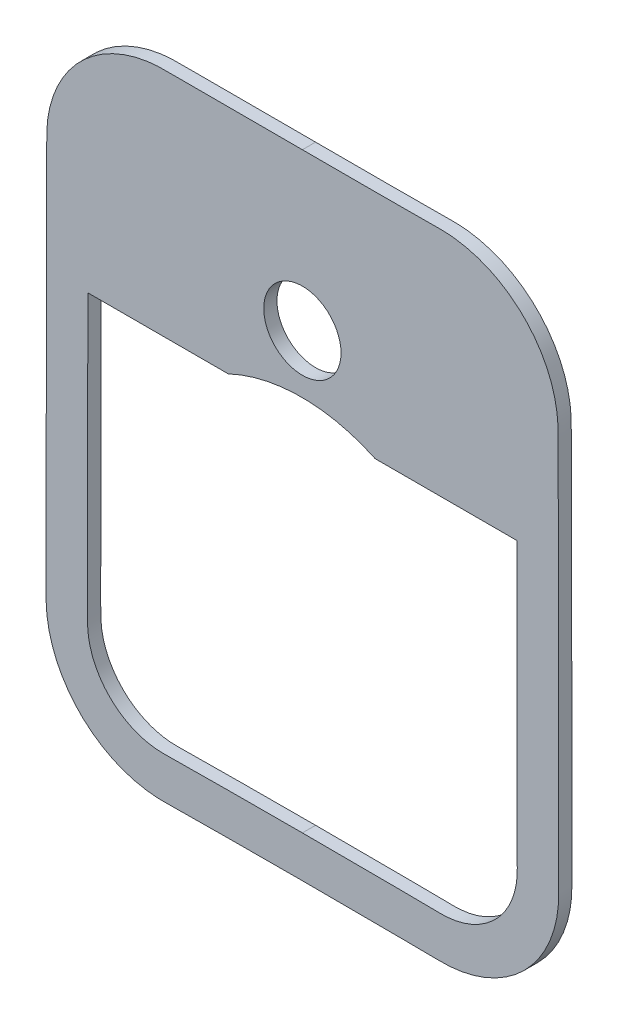
SolidWorks part; units mm, degrees
material "Фанера"
ref_plane "Front Plane" through (0, 0, 0) normal (0, 0, 1) x (1, 0, 0)
ref_plane "Top Plane" through (0, 0, 0) normal (0, 1, 0) x (1, 0, 0)
ref_plane "Right Plane" through (0, 0, 0) normal (1, 0, 0) x (0, 0, -1)
sketch "Эскиз1" plane through (0, 0, 0) normal (0, 0, 1) x (1, 0, 0)
  line L0 (-45.5461, 87.8348) -> (-15.7339, 87.8348)
  line L1 (15.434, 87.8348) -> (45.5461, 87.8348)
  circle A1 centre (0, 103.6369) radius 5.3081 construction
  circle A2 centre (0, 103.6369) radius 8.2
  arc A3 (15.434, 87.8348) -> (-15.7339, 87.8348) centre (-0.1499, 54.9069) ccw
  spline S2 degree 3 poles (0, 136.1045) (-1.239, 136.1005) (-3.4812, 136.0933) (-6.8233, 136.088) (-10.0686, 136.0864) (-13.4447, 136.0887) (-16.829, 136.0949) (-20.1617, 136.1046) (-23.5121, 136.1176) (-26.2938, 136.1309) (-28.566, 136.1434) (-29.8936, 136.1508) (-31.0537, 136.0882) (-32.1737, 135.9898) (-34.2507, 135.6881) (-36.962, 134.9957) (-40.5448, 133.5311) (-44.1262, 131.3165) (-47.4363, 128.2452) (-49.8603, 125.0096) (-51.5505, 121.7952) (-52.4886, 119.1589) (-53.011, 117.0051) (-53.2597, 115.5274) (-53.3997, 114.2038) (-53.4667, 113.0773) (-53.471, 112.0145) (-53.4746, 110.9498) (-53.4785, 109.8154) (-53.4833, 108.4239) (-53.4925, 105.7023) (-53.5036, 102.2993) (-53.5196, 97.2001) (-53.5364, 91.538) (-53.5543, 84.7858) (-53.5702, 77.9771) (-53.5877, 68.9188) (-53.602, 57.5219) (-53.6068, 47.3771) (-53.6075, 40.6409) (-53.6074, 37.3029) (-53.607, 33.8361) (-53.6056, 31.1139) (-53.6056, 29.1689) (-53.6031, 28.0347) (-53.6112, 26.7796) (-53.557, 25.5233) (-53.4451, 24.3914) (-53.1914, 22.5697) (-52.5939, 20.0135) (-51.2863, 16.6996) (-49.5197, 13.6361) (-47.2969, 10.8371) (-44.7104, 8.4168) (-41.7685, 6.386) (-38.5802, 4.8214) (-35.772, 3.927) (-33.4615, 3.4583) (-31.7903, 3.2468) (-30.0031, 3.1418) (-28.4368, 3.1717) (-26.9773, 3.1851) (-25.8041, 3.1977) (-23.8503, 3.2174) (-19.9413, 3.254) (-14.0761, 3.2944) (-8.2109, 3.3181) (-3.5189, 3.3246) (-1.173, 3.3237) (0, 3.3232) knots 0 0 0 0 0.016944 0.030662 0.045705 0.061325 0.076832 0.091987 0.106901 0.12265 0.130027 0.137979 0.140797 0.145912 0.153349 0.169481 0.184029 0.206151 0.226649 0.24543 0.261159 0.276148 0.283562 0.291448 0.296618 0.30176 0.306873 0.311149 0.316321 0.322385 0.330179 0.353541 0.368923 0.399912 0.430974 0.461263 0.493024 0.55485 0.61712 0.631758 0.64697 0.66277 0.679167 0.684198 0.689368 0.694679 0.70136 0.706552 0.710228 0.726511 0.7423 0.758789 0.774686 0.791009 0.80705 0.823397 0.8394 0.847199 0.855617 0.862414 0.871663 0.877028 0.882376 0.887707 0.90375 0.935835 0.967918 0.983959 1 1 1 1 construction
  spline S3 degree 3 poles (0, 3.3232) (1.137, 3.3237) (3.411, 3.3246) (7.9589, 3.3186) (12.568, 3.3008) (17.1159, 3.2733) (19.9367, 3.2523) (22.1494, 3.2332) (23.7247, 3.2185) (25.4517, 3.2014) (27.0575, 3.1842) (28.6039, 3.169) (29.7408, 3.1532) (30.8236, 3.1871) (31.9058, 3.2668) (33.0392, 3.4068) (34.8562, 3.7148) (37.397, 4.3882) (40.5436, 5.7219) (43.4912, 7.5042) (46.1307, 9.6661) (48.4515, 12.1944) (50.3766, 15.0068) (51.8999, 18.0934) (52.7772, 20.776) (53.2576, 23.0208) (53.4959, 24.7163) (53.6141, 26.4623) (53.6032, 27.9573) (53.6057, 29.3141) (53.6056, 30.6272) (53.6063, 32.0893) (53.6067, 33.6016) (53.6074, 36.8843) (53.6078, 44.2661) (53.6034, 55.7555) (53.5877, 69.5428) (53.5639, 81.0461) (53.54, 90.2376) (53.5223, 96.3284) (53.5057, 101.6388) (53.4909, 106.2346) (53.4794, 109.4872) (53.4731, 111.3988) (53.4706, 111.9699) (53.4708, 112.6573) (53.4454, 113.462) (53.3764, 114.4711) (53.2466, 115.5902) (53.0551, 116.7225) (52.6709, 118.4974) (51.883, 121.0078) (49.9426, 125.0318) (46.3561, 129.6525) (41.6689, 133.0142) (37.3179, 134.8795) (34.2664, 135.7038) (31.9363, 136.025) (30.5022, 136.122) (29.6264, 136.1507) (28.7596, 136.1442) (27.9312, 136.1399) (26.6088, 136.1326) (24.8092, 136.1237) (22.5484, 136.1138) (19.9534, 136.1041) (16.9679, 136.0953) (13.5551, 136.0889) (10.1506, 136.0863) (6.8791, 136.0879) (3.51, 136.0932) (1.2495, 136.1005) (0, 136.1045) knots 0 0 0 0 0.015551 0.031101 0.062202 0.07859 0.093303 0.100784 0.108854 0.114851 0.124405 0.130817 0.136003 0.139953 0.145631 0.150838 0.155566 0.170832 0.186659 0.20215 0.217786 0.233163 0.248936 0.264236 0.280092 0.287391 0.295615 0.303487 0.311301 0.316057 0.322045 0.32926 0.336053 0.342729 0.374158 0.437014 0.499871 0.562728 0.594345 0.625584 0.646032 0.666977 0.688441 0.690519 0.693122 0.696252 0.699919 0.704131 0.710083 0.71532 0.71983 0.734917 0.751172 0.780732 0.813908 0.82875 0.845335 0.856962 0.860863 0.864992 0.868942 0.872718 0.876322 0.887028 0.897332 0.907244 0.92252 0.938164 0.953922 0.969083 0.98291 1 1 1 1 construction
  spline S4 degree 1 poles (0, 11.3232) (0, 128.1045) knots 0 0 1 1 construction
  spline S5 degree 1 poles (0, 128.1045) (0, 11.3232) knots 0 0 1 1 construction
  spline S6 degree 3 poles (0, 11.3232) (2.2914, 11.3241) (6.8725, 11.3235) (12.6076, 11.3006) (17.1907, 11.273) (20.6304, 11.2473) (23.4945, 11.2214) (25.5015, 11.2012) (26.6445, 11.1892) (27.4981, 11.1803) (28.3526, 11.1721) (29.2615, 11.1598) (29.839, 11.1589) (30.5951, 11.1877) (31.5601, 11.2733) (33.0632, 11.5165) (34.9112, 12.0213) (37.7182, 13.2396) (40.8423, 15.4848) (43.2085, 18.527) (44.5303, 21.281) (45.1061, 23.1124) (45.4051, 24.6024) (45.5267, 25.5545) (45.5832, 26.321) (45.6035, 26.858) (45.6071, 27.5423) (45.6037, 28.4431) (45.6056, 29.3042) (45.6057, 30.4331) (45.6062, 31.8704) (45.6067, 33.5791) (45.6072, 35.8647) (45.6075, 38.7185) (45.6074, 42.1445) (45.6068, 45.57) (45.6053, 50.1374) (45.602, 55.8464) (45.5955, 62.6969) (45.5861, 69.5469) (45.5735, 76.397) (45.5611, 81.9221) (45.5502, 86.3057) (45.5431, 88.9766) (45.5331, 92.5859) (45.5226, 96.1952) (45.5096, 100.376) (45.4987, 103.8012) (45.4893, 106.6586) (45.4812, 108.9361) (45.4768, 110.3823) (45.4721, 111.4889) (45.4715, 112.2716) (45.4666, 112.6362) (45.4544, 113.016) (45.4264, 113.485) (45.3721, 114.0493) (45.2726, 114.7975) (45.0279, 116.0922) (44.4738, 117.9106) (43.1792, 120.6556) (40.8322, 123.7098) (37.6799, 125.9932) (34.8772, 127.2283) (33.0188, 127.7525) (31.5003, 128.0116) (30.5513, 128.1064) (29.7599, 128.144) (29.2425, 128.1486) (28.3287, 128.1414) (27.2054, 128.1361) (25.7635, 128.1282) (23.4788, 128.1177) (20.6144, 128.106) (17.18, 128.0957) (12.599, 128.0869) (6.871, 128.0852) (2.2905, 128.0971) (0, 128.1045) knots 0.000014 0.000014 0.000014 0.000014 0.03126 0.062506 0.078129 0.093752 0.109375 0.117186 0.121092 0.124998 0.128903 0.132809 0.136715 0.140621 0.148432 0.156244 0.171867 0.187489 0.218735 0.249981 0.265604 0.281227 0.289039 0.29685 0.300756 0.304661 0.308567 0.312473 0.316379 0.320284 0.328096 0.335907 0.343719 0.359342 0.374965 0.390588 0.40621 0.437456 0.468702 0.499948 0.531194 0.56244 0.575549 0.591172 0.598984 0.624931 0.640554 0.656177 0.6718 0.679612 0.687423 0.691329 0.695235 0.697188 0.69914 0.703046 0.706952 0.710858 0.718669 0.734292 0.749915 0.781161 0.812407 0.82803 0.843652 0.851464 0.859275 0.863181 0.867087 0.870993 0.874898 0.88271 0.890521 0.906144 0.921767 0.93739 0.968636 0.999882 0.999882 0.999882 0.999882
  spline S7 degree 3 poles (0, 128.1045) (-2.2907, 128.0971) (-6.8718, 128.0852) (-12.6006, 128.0869) (-17.1818, 128.0957) (-20.6176, 128.1061) (-23.4795, 128.1176) (-25.77, 128.1283) (-27.1994, 128.1358) (-28.3476, 128.1419) (-29.1907, 128.1474) (-29.8232, 128.1414) (-30.3319, 128.117) (-30.9382, 128.0678) (-31.6906, 127.979) (-33.0225, 127.7517) (-34.8772, 127.2284) (-37.6884, 125.9886) (-40.8219, 123.716) (-43.1706, 120.6707) (-44.4688, 117.9227) (-45.024, 116.1087) (-45.2707, 114.8086) (-45.3699, 114.0685) (-45.4261, 113.488) (-45.4599, 112.9409) (-45.4703, 112.4035) (-45.4724, 111.5273) (-45.4766, 110.3911) (-45.4814, 108.9604) (-45.4892, 106.6773) (-45.4986, 103.8214) (-45.5096, 100.3953) (-45.5225, 96.2082) (-45.5331, 92.5924) (-45.5431, 88.9767) (-45.5502, 86.3115) (-45.5611, 81.9334) (-45.5735, 76.4136) (-45.586, 69.5627) (-45.5954, 62.7117) (-45.602, 55.8605) (-45.606, 49.009) (-45.6074, 43.2988) (-45.6075, 38.731) (-45.6073, 35.8753) (-45.6067, 33.5922) (-45.606, 31.8805) (-45.6056, 30.4454) (-45.6058, 29.3115) (-45.6035, 28.4666) (-45.6068, 27.53) (-45.6045, 26.8932) (-45.5822, 26.3158) (-45.5276, 25.5629) (-45.4066, 24.6111) (-45.1071, 23.1163) (-44.5329, 21.2881) (-43.2102, 18.5291) (-40.8471, 15.4898) (-37.7196, 13.2403) (-34.9165, 12.0232) (-33.0636, 11.5165) (-31.5664, 11.2746) (-30.3948, 11.1683) (-29.3182, 11.1537) (-27.4707, 11.1831) (-25.8, 11.1975) (-23.4923, 11.2217) (-20.6348, 11.2472) (-17.1922, 11.2731) (-12.6093, 11.3005) (-6.8732, 11.3235) (-2.2917, 11.3241) (0, 11.3232) knots 0.000118 0.000118 0.000118 0.000118 0.031364 0.06261 0.078233 0.093856 0.109479 0.11729 0.125102 0.129007 0.132913 0.136819 0.140725 0.14463 0.148536 0.156347 0.17197 0.187593 0.218839 0.250085 0.265708 0.281331 0.289142 0.293048 0.296954 0.30086 0.304765 0.308671 0.312577 0.320388 0.3282 0.343823 0.359446 0.375069 0.401098 0.40891 0.424532 0.43756 0.468806 0.500052 0.531298 0.562544 0.59379 0.625035 0.640658 0.656281 0.664093 0.671904 0.679716 0.683621 0.687527 0.691433 0.695339 0.699244 0.70315 0.710961 0.718773 0.734396 0.750019 0.781265 0.812511 0.828133 0.843756 0.851568 0.859379 0.867191 0.875002 0.882814 0.890625 0.906248 0.921871 0.937494 0.96874 0.999986 0.999986 0.999986 0.999986
  spline S8 degree 1 poles (0, 2.5232) (0, 136.9045) knots 0 0 1 1 construction
  spline S9 degree 1 poles (0, 136.9045) (0, 2.5232) knots 0 0 1 1 construction
  spline S10 degree 3 poles (0, 2.5232) (2.2842, 2.5241) (6.8529, 2.5236) (13.7041, 2.4958) (19.4164, 2.459) (23.9801, 2.4149) (26.846, 2.392) (29.1099, 2.354) (31.4842, 2.3808) (34.4119, 2.7568) (37.8425, 3.6917) (42.1877, 5.5784) (47.0338, 9.0623) (50.6974, 13.7738) (52.746, 18.0449) (53.811, 21.438) (54.2907, 24.3483) (54.4176, 26.7256) (54.3969, 29.0189) (54.409, 31.8702) (54.4058, 36.4421) (54.4082, 42.1536) (54.4059, 49.0088) (54.4008, 58.1486) (54.3875, 69.5736) (54.3641, 80.9985) (54.3402, 90.1385) (54.3208, 96.9928) (54.3011, 102.7067) (54.2894, 107.2733) (54.2705, 110.138) (54.2815, 112.4048) (54.1968, 114.7883) (53.7435, 117.7048) (52.7057, 121.1087) (50.6806, 125.3922) (47.0248, 130.1307) (42.1686, 133.642) (37.8366, 135.5477) (34.4135, 136.5049) (31.4908, 136.9058) (29.1128, 136.9564) (26.8473, 136.9281) (23.9827, 136.9216) (19.4176, 136.9003) (13.7051, 136.8876) (6.853, 136.8851) (2.2843, 136.8971) (0, 136.9045) knots -0.000001 -0.000001 -0.000001 -0.000001 0.031249 0.062499 0.09375 0.109375 0.125 0.132813 0.140625 0.156251 0.171876 0.187501 0.218751 0.250002 0.265627 0.281252 0.296878 0.30469 0.312503 0.328128 0.343753 0.375004 0.406254 0.437504 0.500005 0.562506 0.593756 0.625007 0.656257 0.671882 0.687508 0.69532 0.703133 0.718758 0.734383 0.750009 0.781259 0.812509 0.828135 0.84376 0.859385 0.867198 0.87501 0.890635 0.906261 0.937511 0.968761 1.000012 1.000012 1.000012 1.000012
  spline S11 degree 3 poles (0, 136.9045) (-2.2845, 136.8971) (-6.8538, 136.8851) (-13.7069, 136.8875) (-19.4195, 136.9005) (-23.9864, 136.9212) (-26.8482, 136.9291) (-29.1203, 136.9547) (-31.4936, 136.9065) (-34.4173, 136.5038) (-37.8401, 135.5465) (-42.1739, 133.6388) (-47.0147, 130.1368) (-50.6678, 125.4129) (-52.6978, 121.1291) (-53.7381, 117.7271) (-54.1953, 114.8104) (-54.2802, 112.4276) (-54.2711, 110.1577) (-54.2892, 107.2938) (-54.3011, 102.7263) (-54.3207, 97.0119) (-54.3401, 90.1567) (-54.364, 81.0156) (-54.3875, 69.5894) (-54.4008, 58.163) (-54.4059, 49.0221) (-54.4082, 42.166) (-54.406, 36.454) (-54.4089, 31.8815) (-54.3966, 29.0301) (-54.4177, 26.7347) (-54.292, 24.3609) (-53.8133, 21.4469) (-52.7489, 18.0529) (-50.7019, 13.7806) (-47.0382, 9.0669) (-42.1933, 5.5811) (-37.846, 3.693) (-34.4178, 2.7578) (-31.4861, 2.3811) (-29.1169, 2.3526) (-26.8474, 2.3931) (-23.9836, 2.4144) (-19.4183, 2.4592) (-13.7058, 2.4957) (-6.8537, 2.5236) (-2.2845, 2.5241) (0, 2.5232) knots -0.000012 -0.000012 -0.000012 -0.000012 0.031239 0.062489 0.093739 0.109365 0.12499 0.132802 0.140615 0.15624 0.171865 0.187491 0.218741 0.249991 0.265617 0.281242 0.296867 0.30468 0.312492 0.328118 0.343743 0.374993 0.406244 0.437494 0.499995 0.562496 0.593746 0.624996 0.656247 0.671872 0.687497 0.69531 0.703122 0.718748 0.734373 0.749998 0.781249 0.812499 0.828124 0.843749 0.859375 0.867187 0.875 0.890625 0.90625 0.937501 0.968751 1.000001 1.000001 1.000001 1.000001
  point P14 (0, 0)
  point P15 (0, 0)
  dimension "D3" = 16.4
  dimension "D4" = 15.8022
  dimension "D5" = 24.4676
  dimension "D1" = 8
  dimension "D2" = 0.8
extrude "Бобышка-Вытянуть1" add sketch "Эскиз1" along normal mid plane 2.8 contours S6 S7 L0 A2 | S10 S11 S7 S6
